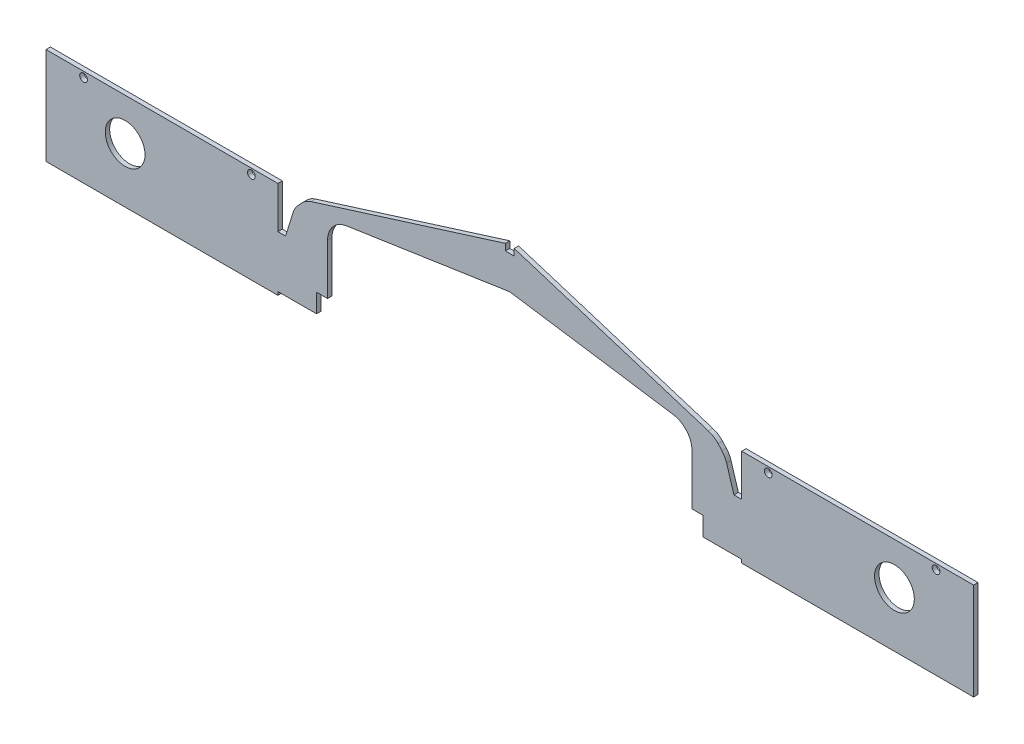
SolidWorks part; units mm, degrees
ref_plane "Piano frontale" through (0, 0, 0) normal (0, 0, 1) x (1, 0, 0)
ref_plane "Piano superiore" through (0, 0, 0) normal (0, 1, 0) x (1, 0, 0)
ref_plane "Piano destro" through (0, 0, 0) normal (1, 0, 0) x (0, 0, -1)
sketch "Schizzo1" plane through (0, 0, 0) normal (0, 0, 1) x (1, 0, 0)
  line L1 (210, -21.95) -> (-210, -21.95)
  line L2 (210, -21.95) -> (210, 21.95)
  line L3 (210, 21.95) -> (-210, 21.95)
  line L4 (-210, -21.95) -> (-210, 21.95)
  line L5 (210, -21.95) -> (-210, 21.95) construction
  line L6 (210, 21.95) -> (-210, -21.95) construction
  point P0 (0, 0)
  dimension "D1" = 43.9
  dimension "D2" = 420
extrude "PiastraBase" add sketch "Schizzo1" along normal blind 2
sketch "Schizzo2" plane through (0, 0, 0) normal (0, 0, -1) x (-1, 0, 0)
  circle A0 centre (-174.1667, 3.05) radius 9
  arc A1 (-171.6667, -7.6621) -> (-176.6667, -7.6621) centre (-174.1667, 3.05) ccw construction
  circle A2 centre (-193, 19.45) radius 1.75
  circle A3 centre (-117, 19.45) radius 1.75
  dimension "D1" = 18
  dimension "D2" = 3.5
extrude "ForoDestro" cut sketch "Schizzo2" against normal through all
mirror "ForoSinistro" about plane through (0, 0, 0) normal (1, 0, 0) of "ForoDestro"
sketch "Schizzo3" plane through (0, 0, 0) normal (0, 0, -1) x (-1, 0, 0)
  line L0 (-105, -21.95) -> (-105, -20.45)
  line L1 (-105, -20.45) -> (-87.5, -20.45)
  line L2 (-87.5, -20.45) -> (-87.5, -11.95)
  line L3 (-87.5, -11.95) -> (-82.5, -11.95)
  line L4 (-82.5, -11.95) -> (-82.5, -20.45)
  line L5 (-82.5, -20.45) -> (82.5, -20.45)
  line L6 (82.5, -20.45) -> (82.5, -11.95)
  line L7 (82.5, -11.95) -> (87.5, -11.95)
  line L8 (87.5, -11.95) -> (87.5, -20.45)
  line L9 (87.5, -20.45) -> (105, -20.45)
  line L10 (105, -20.45) -> (105, -21.95)
  line L11 (105, -21.95) -> (-105, -21.95)
extrude "IntaglioInferiore" cut sketch "Schizzo3" against normal through all
sketch "Schizzo4" plane through (0, 0, 0) normal (0, 0, -1) x (-1, 0, 0)
  line L0 (-105, 21.95) -> (-105, 3.05)
  line L1 (-105, 3.05) -> (-82.5, 3.05)
  line L2 (105, 3.05) -> (105, 21.95)
  line L3 (105, 21.95) -> (-105, 21.95)
  line L4 (-2.5, -20.45) -> (-105, -20.45) construction
  line L6 (-82.5, 3.05) -> (-82.5, -20.45)
  line L7 (-82.5, -20.45) -> (82.5, -20.45)
  line L8 (82.5, 3.05) -> (82.5, -20.45)
  line L9 (-82.5, -20.45) -> (-82.5, -11.95) construction
  line L10 (82.5, 3.05) -> (105, 3.05)
  spline S1 degree 3 poles (-105, 4.0817) (-105, -3.6822) (-105.0001, -11.4461) (-105, -19.21) knots 0 0 0 0 0.023292 0.023292 0.023292 0.023292 construction
  point P3 (0, 21.95)
  point P4 (0, -20.45)
  dimension "D1" = 15
extrude "IntaglioSuperiore" cut sketch "Schizzo4" against normal through all
sketch "Schizzo5" plane through (0, 0, 0) normal (0, 0, -1) x (-1, 0, 0)
  line L0 (-82.5, 3.05) -> (-82.5, 19.55)
  line L1 (-82.5, 19.55) -> (0, 31.95)
  line L2 (0, 25.7192) -> (0, 60.4433) construction
  line L3 (-87.5, -20.45) -> (-105, -20.45) construction
  line L4 (-2, 49.95) -> (-92.5, 21.55)
  line L7 (-92.5, 21.55) -> (-97.5, 16.05)
  line L8 (-97.5, 16.05) -> (-101.5, 3.05)
  line L9 (-105, 3.05) -> (-82.5, 3.05) construction
  line L10 (-101.5, 3.05) -> (-82.5, 3.05)
  line L11 (0, 46.95) -> (0, 31.95)
  line L12 (-2, 49.95) -> (-2, 46.95)
  line L13 (-2, 46.95) -> (0, 46.95)
  dimension "D1" = 10
  dimension "D2" = 40
  dimension "D3" = 15
  dimension "D4" = 3
  dimension "D5" = 2
  dimension "D6" = 13
  dimension "D7" = 4
  dimension "D8" = 5
  dimension "D9" = 19
  dimension "D10" = 5.5
extrude "Estrusione-Estrusione1" add sketch "Schizzo5" against normal up to surface (2 mm away) up to face at (118, -5.87, 2)
fillet "Raccordo2" radius 10 1 edges at (82.5, 19.55, 1)
fillet "Raccordo3" radius 10 2 edges at (92.5, 21.55, 1) (97.5, 16.05, 1)
mirror "Specchia1" about plane through (0, 0, 0) normal (1, 0, 0) of "Raccordo3", "Raccordo2", "Estrusione-Estrusione1"
combine bodies "Abbina1" operation type add bodies to combine 110 106
